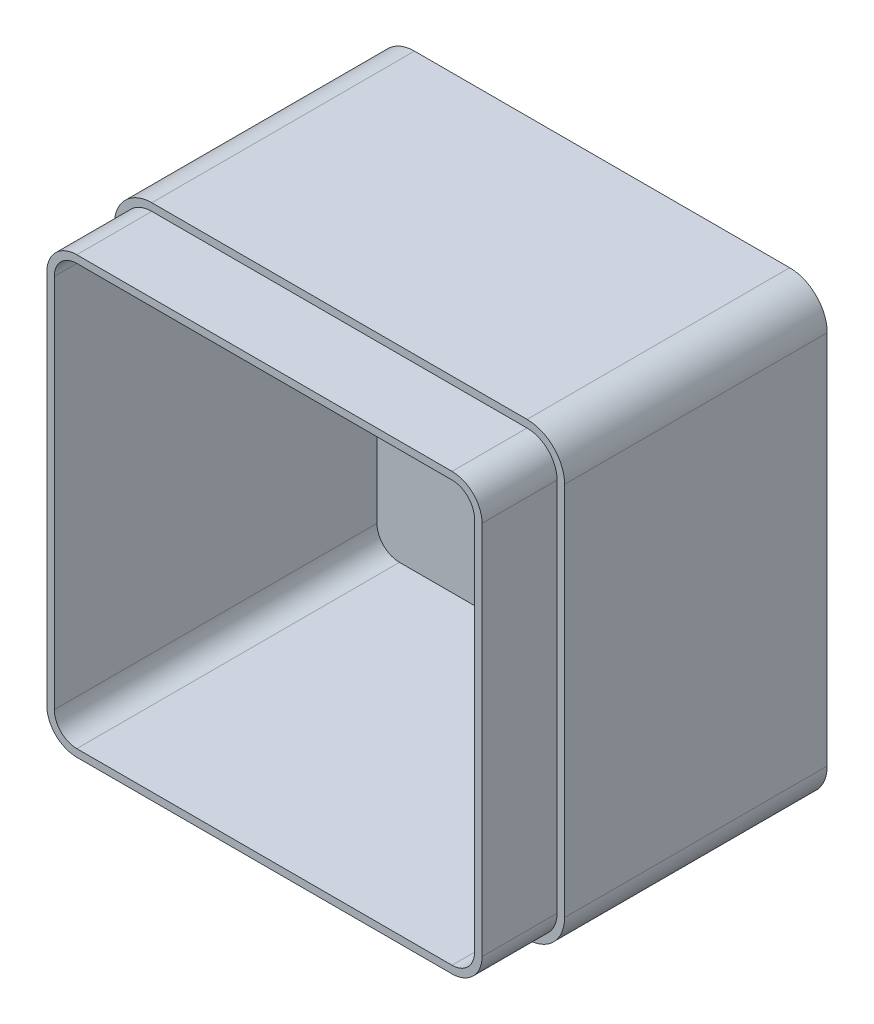
SolidWorks part; units mm, degrees
ref_plane "Front" through (0, 0, 0) normal (0, 0, 1) x (1, 0, 0)
ref_plane "Top" through (0, 0, 0) normal (0, 1, 0) x (1, 0, 0)
ref_plane "Right" through (0, 0, 0) normal (1, 0, 0) x (0, 0, -1)
sketch "Sketch1" plane through (0, 0, 0) normal (0, 0, 1) x (1, 0, 0)
  line L1 (0, 0) -> (120, 0)
  line L2 (0, 0) -> (0, 120)
  line L3 (0, 120) -> (120, 120)
  line L4 (120, 0) -> (120, 120)
  dimension "D1" = 120
  dimension "D2" = 120
extrude "Boss-Extrude1" add sketch "Sketch1" along normal blind 90
fillet "Fillet1" radius 10 4 edges at (0, 0, 45) (120, 0, 45) (0, 120, 45) (120, 120, 45)
shell "Shell1" thickness 4
sketch "Sketch2" plane through (0, 0, 90) normal (0, 0, 1) x (1, 0, 0)
  line L0 (2, 110) -> (2, 10)
  line L1 (10, 2) -> (110, 2)
  line L2 (118, 10) -> (118, 110)
  line L3 (110, 118) -> (10, 118)
  line L4 (0, 110) -> (0, 10)
  line L5 (10, 0) -> (110, 0)
  line L6 (120, 10) -> (120, 110)
  line L7 (110, 120) -> (10, 120)
  line L8 (0, 110) -> (0, 10)
  line L9 (10, 0) -> (110, 0)
  line L10 (120, 10) -> (120, 110)
  line L11 (110, 120) -> (10, 120)
  arc A0 (2, 10) -> (10, 2) centre (10, 10) ccw
  arc A1 (110, 2) -> (118, 10) centre (110, 10) ccw
  arc A2 (118, 110) -> (110, 118) centre (110, 110) ccw
  arc A3 (10, 118) -> (2, 110) centre (10, 110) ccw
  arc A4 (0, 10) -> (10, 0) centre (10, 10) ccw
  arc A5 (110, 0) -> (120, 10) centre (110, 10) ccw
  arc A6 (120, 110) -> (110, 120) centre (110, 110) ccw
  arc A7 (10, 120) -> (0, 110) centre (10, 110) ccw
  arc A8 (0, 10) -> (10, 0) centre (10, 10) ccw
  arc A9 (110, 0) -> (120, 10) centre (110, 10) ccw
  arc A10 (120, 110) -> (110, 120) centre (110, 110) ccw
  arc A11 (10, 120) -> (0, 110) centre (10, 110) ccw
  dimension "D1" = 0
  dimension "D2" = 2
extrude "Cut-Extrude1" cut sketch "Sketch2" against normal blind 20
